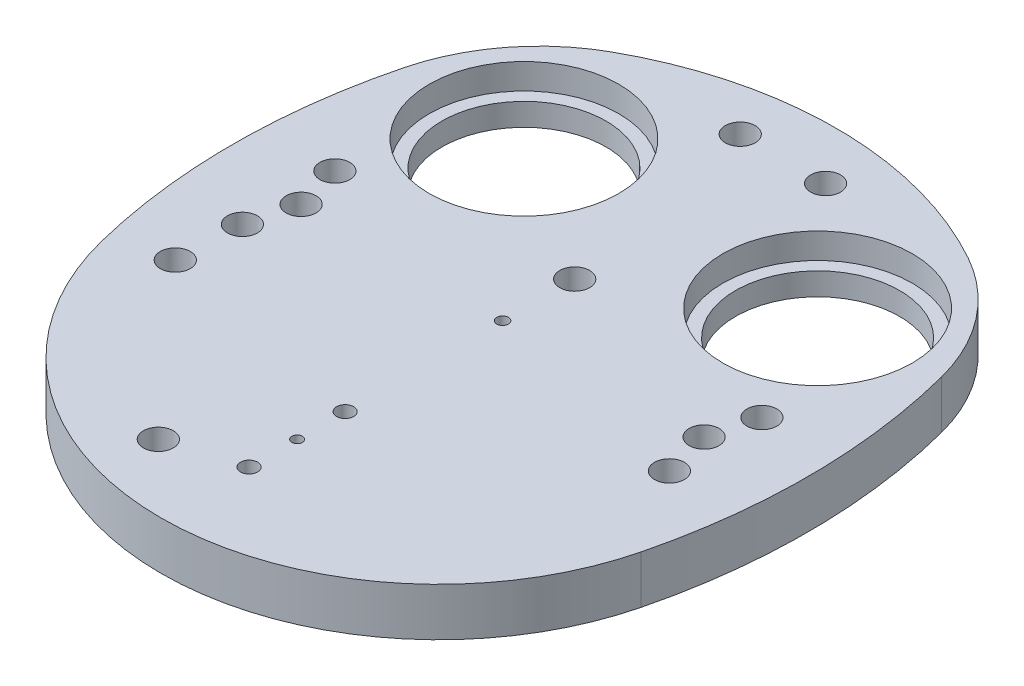
SolidWorks part; units mm, degrees
ref_plane "Front" through (0, 0, 0) normal (0, 0, 1) x (1, 0, 0)
ref_plane "Top" through (0, 0, 0) normal (0, 1, 0) x (1, 0, 0)
ref_plane "Right" through (0, 0, 0) normal (1, 0, 0) x (0, 0, -1)
sketch "Knuckle Spacing" plane through (0, 0, 0) normal (0, 1, 0) x (1, 0, 0)
  line L0 (-27.5, 0) -> (27.5, 0) construction
  line L1 (0, 0) -> (0, -70) construction
  circle A0 centre (-27.5, 0) radius 15 construction
  circle A1 centre (27.5, 0) radius 15 construction
  circle A2 centre (0, -70) radius 15 construction
  dimension "D3" = 30
  dimension "D1" = 55
  dimension "D2" = 70
sketch "XL320" plane through (0, 0, 0) normal (0, 1, 0) x (1, 0, 0)
  line L0 (-0.4, -12) -> (-36.4, 12) construction
  line L1 (-36.4, -12) -> (-0.4, 12) construction
  line L2 (-0.4, 12) -> (-0.4, -12)
  line L3 (-0.4, -12) -> (-36.4, -12)
  line L4 (-36.4, 12) -> (-36.4, -12)
  line L5 (-36.4, 12) -> (-0.4, 12)
  line L6 (-27.5, 0) -> (27.5, 0) construction
  line L7 (0.4, 12) -> (36.4, -12) construction
  line L8 (36.4, -12) -> (36.4, 12)
  line L9 (36.4, 12) -> (0.4, 12)
  line L10 (0.4, -12) -> (36.4, 12) construction
  line L11 (36.4, -12) -> (0.4, -12)
  line L12 (0.4, 12) -> (0.4, -12)
  circle A0 centre (-27.5, 0) radius 8.9
  circle A1 centre (27.5, 0) radius 8.9
  point P10 (-18.4, 0)
  point P17 (18.4, 0)
  dimension "D1" = 17.8
  dimension "D4" = 17.8
  dimension "D2" = 36
  dimension "D3" = 24
  dimension "D5" = 36
  dimension "D6" = 24
sketch "Sketch1" plane through (0, 0, 0) normal (0, 1, 0) x (1, 0, 0)
  line L0 (0, 0) -> (0, -70) construction
  circle A0 centre (-27.5, 0) radius 17.75
  circle A1 centre (27.5, 0) radius 17.75
  circle A2 centre (27.5, 0) radius 20
  circle A3 centre (-27.5, 0) radius 20
  arc A4 (48.5499, -55.5542) -> (46.555, 6.0751) centre (-61.1312, -28.2576) ccw
  arc A5 (-39.2984, 16.1492) -> (39.2984, 16.1492) centre (0, -37.641) cw
  arc A6 (-48.5499, -55.5542) -> (-46.555, 6.0751) centre (61.1312, -28.2576) cw
  arc A7 (48.5499, -55.5542) -> (-48.5499, -55.5542) centre (0, -43.4715) cw
  dimension "D1" = 35.5
  dimension "D2" = 40
  dimension "D3" = 66.6164
  dimension "D5" = 113.0268
  dimension "D6" = 113.0268
  dimension "D7" = 50.0309
  dimension "D4" = 122.2625
extrude "Boss-Extrude1" add sketch "Sketch1" along normal blind 9 contours A7 A4 A2 A5 A3 A6 | A3 A0 | A2 A1
sketch "Sketch2" plane through (0, 0, 0) normal (0, 1, 0) x (1, 0, 0)
  circle A0 centre (-27.5, 0) radius 15.375
  circle A1 centre (27.5, 0) radius 15.375
  circle A2 centre (-27.5, 0) radius 17.75
  circle A3 centre (27.5, 0) radius 17.75
  dimension "D1" = 30.75
  dimension "D2" = 35.5
extrude "Boss-Extrude3" add sketch "Sketch2" along normal blind 4.215
sketch "Sketch3" plane through (0, 9, 0) normal (0, 1, 0) x (1, 0, 0)
  circle A0 centre (-27.5, 0) radius 17.75
  circle A1 centre (27.5, 0) radius 17.75
  dimension "D1" = 35.5
sketch "Sketch4" plane through (0, 9, 0) normal (0, 1, 0) x (1, 0, 0)
  line L0 (0, 0) -> (0, -70) construction
  line L1 (0, 0) -> (0, -70) construction
  line L2 (-27.5, 0) -> (27.5, 0) construction
  circle A0 centre (-8, 21.01) radius 2.8
  circle A2 centre (0, -18) radius 2.8
  circle A3 centre (-40, -22.9303) radius 2.8
  circle A4 centre (-37.75, -31.5038) radius 2.8
  circle A5 centre (-40, -40.255) radius 2.8
  circle A6 centre (-40.5, -52.3285) radius 2.8
  circle A7 centre (-13, -83) radius 2.8
  circle A9 centre (40, -40.255) radius 2.8
  circle A10 centre (37.75, -31.5038) radius 2.8
  circle A11 centre (40, -22.9303) radius 2.8
  circle A12 centre (8, 21.01) radius 2.8
  dimension "D1" = 5.6
  dimension "D3" = 21.01
  dimension "D2" = 19.5
  dimension "D4" = 18
  dimension "D5" = 22.9303
  dimension "D6" = 40
  dimension "D7" = 37.75
  dimension "D8" = 40.255
  dimension "D9" = 40
  dimension "D10" = 8.5735
  dimension "D11" = 12.0735
  dimension "D12" = 40.5
  dimension "D13" = 13
  dimension "D14" = 13
extrude "M3_Tapping_Insert_Holes" cut sketch "Sketch4" against normal blind 7
sketch "Sketch5" plane through (0, 9, 0) normal (0, 1, 0) x (1, 0, 0)
  line L0 (0, 0) -> (0, -70) construction
  line L1 (0, 0) -> (0, -8.2743) construction
  line L2 (0, -8.2743) -> (-16.3604, -8.2743) construction
  line L3 (0, -8.2743) -> (16.3604, -8.2743) construction
  arc A0 (-50.2517, 0.4655) -> (-33.3942, 22.301) centre (-16.3604, -8.2743) cw
  arc A1 (50.2517, 0.4655) -> (33.3942, 22.301) centre (16.3604, -8.2743) ccw
  arc A2 (-33.3942, 22.301) -> (33.3942, 22.301) centre (0, -37.641) cw
  arc A3 (-50.2517, 0.4655) -> (-50.4907, -56.0372) centre (61.1312, -28.2576) ccw
  arc A4 (50.2517, 0.4655) -> (50.4907, -56.0372) centre (-61.1312, -28.2576) cw
  arc A6 (-50.4907, -56.0372) -> (50.4907, -56.0372) centre (0, -43.4715) ccw
  arc A7 (48.5499, -55.5542) -> (46.555, 6.0751) centre (-61.1312, -28.2576) ccw
  arc A11 (-48.5499, -55.5542) -> (48.5499, -55.5542) centre (0, -43.4715) ccw construction
  arc A12 (39.2984, 16.1492) -> (-39.2984, 16.1492) centre (0, -37.641) ccw construction
  arc A15 (-46.555, 6.0751) -> (-48.5499, -55.5542) centre (61.1312, -28.2576) ccw
  arc A16 (-46.555, 6.0751) -> (-48.5499, -55.5542) centre (61.1312, -28.2576) ccw construction
  arc A17 (-48.5499, -55.5542) -> (48.5499, -55.5542) centre (0, -43.4715) ccw
  arc A18 (-39.2984, 16.1492) -> (39.2984, 16.1492) centre (0, -37.641) cw
  circle A19 centre (27.5, 0) radius 20 construction
  arc A20 (39.2984, 16.1492) -> (46.555, 6.0751) centre (27.5, 0) cw
  arc A21 (-46.555, 6.0751) -> (-39.2984, 16.1492) centre (-27.5, 0) cw
  point P17 (0, -93.5023)
  point P18 (0, -95.5023)
  point P22 (0, 30.9755)
  point P23 (0, 28.9755)
  dimension "D1" = 35
  dimension "D2" = 35
  dimension "D4" = 2
  dimension "D5" = 52.0309
  dimension "D6" = 16.3604
  dimension "D8" = 115.0268
  dimension "D9" = 115.0268
  dimension "D10" = 8.2743
extrude "Extrude-Thin2" add sketch "Sketch5" against normal blind 9 thin contours A20 A18 A21 A15 A17 A7 | A4 A6 A3 A0 A2 A1
sketch "Sketch7" plane through (0, 9, 0) normal (0, 1, 0) x (1, 0, 0)
  circle A0 centre (0, -70) radius 15.25
  dimension "D1" = 30.5
extrude "Thumb_Knuckle_Hole" cut sketch "Sketch7" against normal through all from offset 4.5875 offset against normal yes
sketch "Sketch8" plane through (0, 9, 0) normal (0, 1, 0) x (1, 0, 0)
  line L0 (0, 0) -> (0, -70) construction
  circle A0 centre (0, -70) radius 1
  circle A1 centre (0, -61) radius 1.6
  circle A2 centre (0, -79) radius 1.6
  dimension "D1" = 3.2
  dimension "D3" = 2
  dimension "D4" = 3.2
  dimension "D2" = 9
  dimension "D5" = 9
extrude "Thumb_Through_Hole(s)" cut sketch "Sketch8" against normal through all
sketch "Sketch9" plane through (0, 9, 0) normal (0, 1, 0) x (1, 0, 0)
  line L0 (0, -18) -> (0, -31.5038) construction
  line L1 (0, 0) -> (0, -70) construction
  circle A0 centre (0, -31.5038) radius 1.1
  dimension "D1" = 2.2
  dimension "D2" = 13.5038
extrude "Center_Screw_Through" cut sketch "Sketch9" against normal through all
